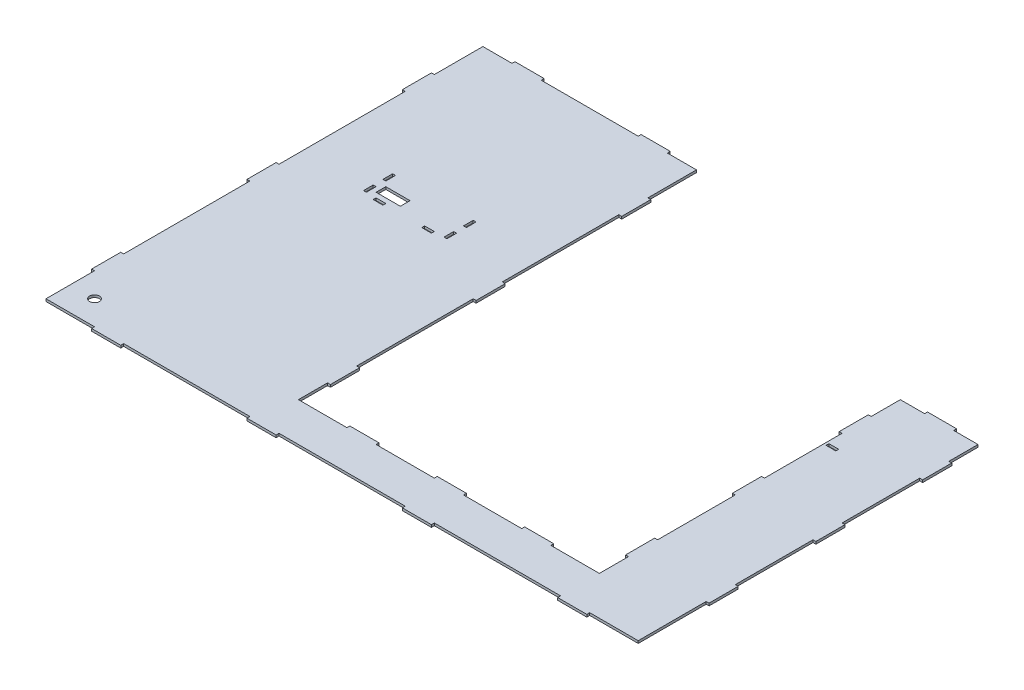
SolidWorks part; units mm, degrees
material "ABS"
ref_plane "Front Plane" through (0, 0, 0) normal (0, 0, 1) x (1, 0, 0)
ref_plane "Top Plane" through (0, 0, 0) normal (0, 1, 0) x (1, 0, 0)
ref_plane "Right Plane" through (0, 0, 0) normal (1, 0, 0) x (0, 0, -1)
sketch "Sketch1" plane through (0, 0, 0) normal (0, 1, 0) x (1, 0, 0)
  line L0 (0, 0) -> (0, 50)
  line L1 (0, 450) -> (30, 450)
  line L2 (220, 450) -> (220, 400)
  line L3 (220, 40) -> (270, 40)
  line L5 (610, 0) -> (560, 0)
  line L6 (530, 40) -> (530, 70)
  line L7 (530, 350) -> (555, 350)
  line L8 (610, 0) -> (610, 70)
  line L9 (220, 70) -> (220, 40)
  line L10 (-3, 400) -> (0, 400)
  line L11 (-3, 400) -> (-3, 370)
  line L12 (-3, 370) -> (0, 370)
  line L14 (-3, 240) -> (0, 240)
  line L15 (-3, 240) -> (-3, 210)
  line L16 (-3, 210) -> (0, 210)
  line L18 (-3, 80) -> (0, 80)
  line L19 (-3, 80) -> (-3, 50)
  line L20 (-3, 50) -> (0, 50)
  line L34 (220, 400) -> (223, 400)
  line L36 (220, 370) -> (223, 370)
  line L37 (223, 400) -> (223, 370)
  line L38 (220, 250) -> (223, 250)
  line L40 (220, 220) -> (223, 220)
  line L41 (223, 250) -> (223, 220)
  line L42 (220, 100) -> (223, 100)
  line L44 (220, 70) -> (223, 70)
  line L45 (223, 100) -> (223, 70)
  line L46 (610, 320) -> (613, 320)
  line L48 (610, 290) -> (613, 290)
  line L49 (613, 320) -> (613, 290)
  line L50 (610, 210) -> (613, 210)
  line L52 (610, 180) -> (613, 180)
  line L53 (613, 210) -> (613, 180)
  line L58 (610, 100) -> (613, 100)
  line L60 (610, 70) -> (613, 70)
  line L61 (613, 100) -> (613, 70)
  line L62 (530, 320) -> (527, 320)
  line L64 (530, 290) -> (527, 290)
  line L65 (527, 320) -> (527, 290)
  line L66 (530, 210) -> (527, 210)
  line L68 (530, 180) -> (527, 180)
  line L69 (527, 210) -> (527, 180)
  line L70 (530, 100) -> (527, 100)
  line L72 (530, 70) -> (527, 70)
  line L73 (527, 100) -> (527, 70)
  line L74 (220, 220) -> (220, 100)
  line L75 (220, 370) -> (220, 250)
  line L76 (530, 100) -> (530, 180)
  line L78 (530, 320) -> (530, 350)
  line L79 (610, 320) -> (610, 350)
  line L80 (610, 210) -> (610, 290)
  line L81 (610, 100) -> (610, 180)
  line L82 (0, 80) -> (0, 210)
  line L83 (0, 240) -> (0, 370)
  line L84 (0, 400) -> (0, 450)
  line L85 (190, 450) -> (220, 450)
  line L87 (30, 450) -> (30, 453)
  line L88 (30, 453) -> (60, 453)
  line L89 (60, 450) -> (60, 453)
  line L91 (160, 450) -> (160, 453)
  line L92 (160, 453) -> (190, 453)
  line L93 (190, 450) -> (190, 453)
  line L94 (60, 450) -> (160, 450)
  line L95 (585, 350) -> (610, 350)
  line L97 (555, 350) -> (555, 353)
  line L98 (555, 353) -> (585, 353)
  line L99 (585, 350) -> (585, 353)
  line L100 (300, 40) -> (360, 40)
  line L102 (270, 40) -> (270, 43)
  line L103 (270, 43) -> (300, 43)
  line L104 (300, 40) -> (300, 43)
  line L106 (450, 40) -> (450, 43)
  line L107 (450, 43) -> (480, 43)
  line L108 (480, 40) -> (480, 43)
  line L110 (360, 40) -> (360, 43)
  line L111 (360, 43) -> (390, 43)
  line L112 (390, 40) -> (390, 43)
  line L113 (390, 40) -> (450, 40)
  line L114 (480, 40) -> (530, 40)
  line L115 (50, 0) -> (0, 0)
  line L117 (50, 0) -> (50, -3)
  line L118 (50, -3) -> (80, -3)
  line L119 (80, 0) -> (80, -3)
  line L121 (370, 0) -> (370, -3)
  line L122 (370, -3) -> (400, -3)
  line L123 (400, 0) -> (400, -3)
  line L125 (530, 0) -> (530, -3)
  line L126 (530, -3) -> (560, -3)
  line L127 (560, 0) -> (560, -3)
  line L129 (210, 0) -> (210, -3)
  line L130 (210, -3) -> (240, -3)
  line L131 (240, 0) -> (240, -3)
  line L132 (210, 0) -> (80, 0)
  line L133 (370, 0) -> (240, 0)
  line L134 (530, 0) -> (400, 0)
  line L135 (110, 450) -> (110, 280) construction
  line L136 (67, 270) -> (70, 270)
  line L137 (67, 270) -> (67, 260)
  line L138 (67, 260) -> (70, 260)
  line L139 (70, 270) -> (70, 260)
  line L140 (67, 290) -> (70, 290)
  line L141 (67, 290) -> (67, 280)
  line L142 (67, 280) -> (70, 280)
  line L143 (70, 290) -> (70, 280)
  line L148 (80, 260) -> (90, 260)
  line L149 (80, 260) -> (80, 257)
  line L150 (80, 257) -> (90, 257)
  line L151 (90, 260) -> (90, 257)
  line L152 (140, 260) -> (130, 260)
  line L153 (140, 260) -> (140, 257)
  line L154 (140, 257) -> (130, 257)
  line L155 (130, 260) -> (130, 257)
  line L160 (153, 260) -> (150, 260)
  line L161 (150, 270) -> (150, 260)
  line L162 (153, 270) -> (153, 260)
  line L163 (153, 270) -> (150, 270)
  line L164 (153, 280) -> (150, 280)
  line L165 (150, 290) -> (150, 280)
  line L166 (153, 290) -> (153, 280)
  line L167 (153, 290) -> (150, 290)
  line L173 (530, 210) -> (530, 290)
  point P106 (135, 257)
  point P118 (0, 0)
  dimension "D1" = 220
  dimension "D2" = 610
  dimension "D3" = 450
  dimension "D4" = 350
  dimension "D5" = 80
  dimension "D6" = 40
  dimension "D7" = 30
  dimension "D8" = 3
  dimension "D9" = 30
  dimension "D10" = 50
  dimension "D11" = 3
  dimension "D12" = 30
  dimension "D13" = 30
  dimension "D14" = 130
  dimension "D15" = 30
  dimension "D16" = 3
  dimension "D17" = 3
  dimension "D18" = 50
  dimension "D19" = 3
  dimension "D20" = 30
  dimension "D21" = 30
  dimension "D22" = 3
  dimension "D23" = 50
  dimension "D24" = 120
  dimension "D25" = 120
  dimension "D26" = 30
  dimension "D27" = 3
  dimension "D28" = 30
  dimension "D29" = 3
  dimension "D30" = 3
  dimension "D31" = 30
  dimension "D32" = 30
  dimension "D33" = 3
  dimension "D34" = 80
  dimension "D35" = 3
  dimension "D36" = 30
  dimension "D37" = 3
  dimension "D38" = 3
  dimension "D39" = 80
  dimension "D40" = 3
  dimension "D41" = 30
  dimension "D42" = 30
  dimension "D43" = 30
  dimension "D44" = 3
  dimension "D45" = 80
  dimension "D46" = 3
  dimension "D47" = 30
  dimension "D48" = 80
  dimension "D49" = 30
  dimension "D50" = 30
  dimension "D51" = 30
  dimension "D52" = 3
  dimension "D53" = 25
  dimension "D54" = 30
  dimension "D55" = 30
  dimension "D56" = 30
  dimension "D57" = 3
  dimension "D58" = 3
  dimension "D59" = 3
  dimension "D60" = 50
  dimension "D61" = 50
  dimension "D62" = 60
  dimension "D63" = 3
  dimension "D64" = 30
  dimension "D65" = 30
  dimension "D66" = 30
  dimension "D67" = 30
  dimension "D68" = 3
  dimension "D69" = 3
  dimension "D70" = 3
  dimension "D71" = 50
  dimension "D72" = 50
  dimension "D73" = 130
  dimension "D74" = 130
  dimension "D75" = 10
  dimension "D76" = 260
  dimension "D77" = 3
  dimension "D78" = 67
  dimension "D79" = 10
  dimension "D80" = 3
  dimension "D81" = 10
  dimension "D82" = 67
  dimension "D83" = 10
  dimension "D84" = 3
  dimension "D85" = 10
  dimension "D87" = 10
  dimension "D88" = 10
  dimension "D91" = 3
  dimension "D93" = 3
  dimension "D94" = 0
extrude "Boss-Extrude1" add sketch "Sketch1" along normal blind 2.5
sketch "Sketch2" plane through (0, 2.5, 0) normal (0, 1, 0) x (1, 0, 0)
  line L0 (530, 210) -> (530, 290) construction
  line L1 (532.5, 274) -> (542.5, 274)
  line L2 (532.5, 274) -> (532.5, 271)
  line L3 (532.5, 271) -> (542.5, 271)
  line L4 (542.5, 274) -> (542.5, 271)
  line L5 (530, 350) -> (555, 350) construction
  dimension "D1" = 10
  dimension "D2" = 3
  dimension "D3" = 2.5
  dimension "D4" = 76
extrude "Cut-Extrude1" cut sketch "Sketch2" against normal blind 10
sketch "Sketch3" plane through (0, 0, 0) normal (0, -1, 0) x (1, 0, 0)
  line L0 (50, 0) -> (0, 0) construction
  line L1 (0, 0) -> (0, -50) construction
  line L2 (80, -260) -> (90, -260) construction
  line L3 (75, -265) -> (100, -265)
  line L4 (75, -265) -> (75, -275)
  line L5 (75, -275) -> (100, -275)
  line L6 (100, -265) -> (100, -275)
  line L7 (70, -270) -> (70, -260) construction
  circle A0 centre (25, -25) radius 5
  point P12 (85, -260)
  dimension "D1" = 10
  dimension "D2" = 25
  dimension "D3" = 25
  dimension "D4" = 25
  dimension "D5" = 10
  dimension "D6" = 5
  dimension "D7" = 5
extrude "Cut-Extrude2" cut sketch "Sketch3" against normal blind 10
